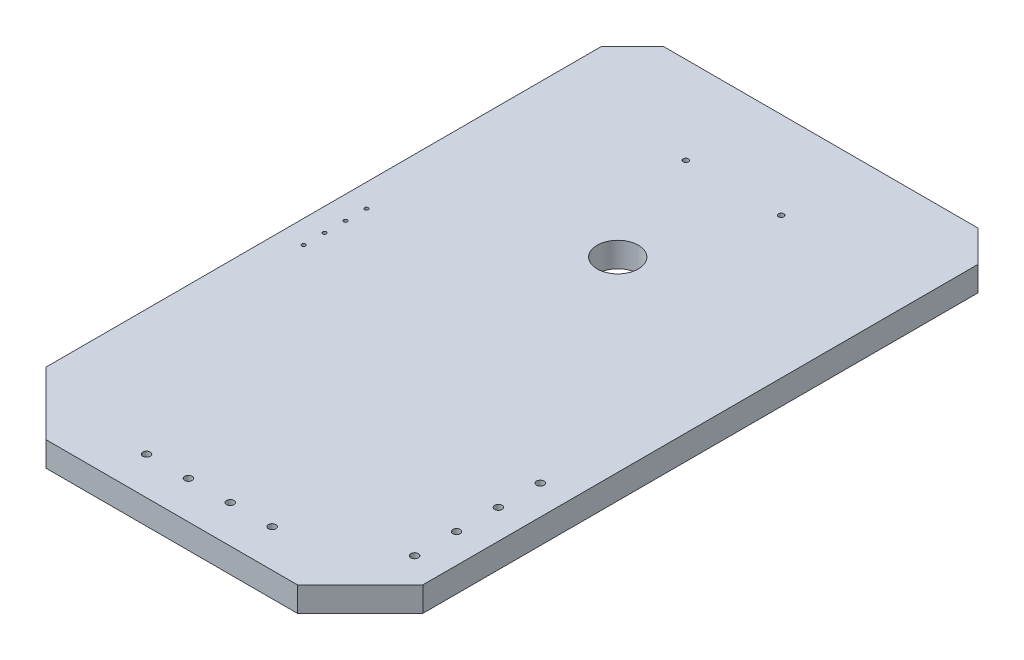
SolidWorks part; units mm, degrees
ref_plane "前视基准面" through (0, 0, 0) normal (0, 0, 1) x (1, 0, 0)
ref_plane "上视基准面" through (0, 0, 0) normal (0, 1, 0) x (1, 0, 0)
ref_plane "右视基准面" through (0, 0, 0) normal (1, 0, 0) x (0, 0, -1)
sketch "草图1" plane through (0, 0, 0) normal (0, 1, 0) x (1, 0, 0)
  line L0 (139.065, 95.25) -> (120.015, 95.25)
  line L1 (118.11, 59.69) -> (118.11, 93.345)
  line L2 (120.015, 95.25) -> (118.11, 93.345)
  line L21 (118.11, 59.69) -> (121.92, 55.88)
  line L22 (137.16, 55.88) -> (140.97, 59.69)
  line L23 (121.92, 55.88) -> (137.16, 55.88)
  line L25 (139.065, 95.25) -> (140.97, 93.345)
  line L26 (140.97, 59.69) -> (140.97, 93.345)
  circle A138 centre (126.652, 89.949) radius 0.1625
  circle A139 centre (132.428, 89.949) radius 0.1625
  circle A140 centre (133.35, 58.166) radius 0.225
  circle A141 centre (130.81, 58.166) radius 0.225
  circle A142 centre (128.27, 58.166) radius 0.225
  circle A143 centre (125.73, 58.166) radius 0.225
  circle A144 centre (139.192, 68.58) radius 0.225
  circle A145 centre (139.192, 66.04) radius 0.225
  circle A146 centre (139.192, 63.5) radius 0.225
  circle A147 centre (139.192, 60.96) radius 0.225
  circle A242 centre (119.507, 77.724) radius 0.1125
  circle A243 centre (119.507, 76.454) radius 0.1125
  circle A244 centre (119.507, 73.914) radius 0.1125
  circle A245 centre (119.507, 75.184) radius 0.1125
extrude "凸台-拉伸1" add sketch "草图1" along normal blind 1.5
sketch "草图2" plane through (0, 1.5, 0) normal (0, 1, 0) x (1, 0, 0)
  circle A10 centre (129.667, 82.804) radius 1.25
extrude "切除-拉伸1" cut sketch "草图2" against normal through all
